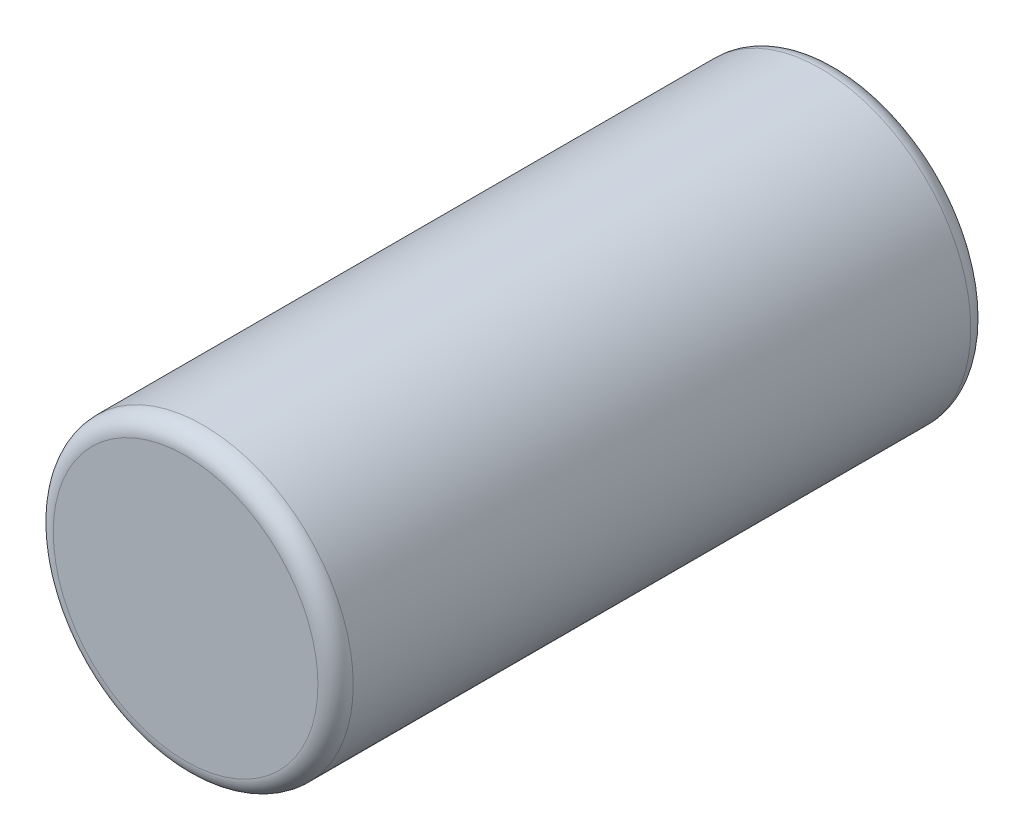
SolidWorks part; units mm, degrees
ref_plane "Front" through (0, 0, 0) normal (0, 0, 1) x (1, 0, 0)
ref_plane "Top" through (0, 0, 0) normal (0, 1, 0) x (1, 0, 0)
ref_plane "Right" through (0, 0, 0) normal (1, 0, 0) x (0, 0, -1)
sketch "Эскиз1" plane through (0, 0, 0) normal (0, 0, 1) x (1, 0, 0)
  circle A0 centre (0, 0) radius 8.5
  dimension "D1" = 17
extrude "Бобышка-Вытянуть1" add sketch "Эскиз1" along normal blind 37
fillet "Скругление1" radius 1 2 edges at (8.5, 0, 0) (8.5, 0, 37)
